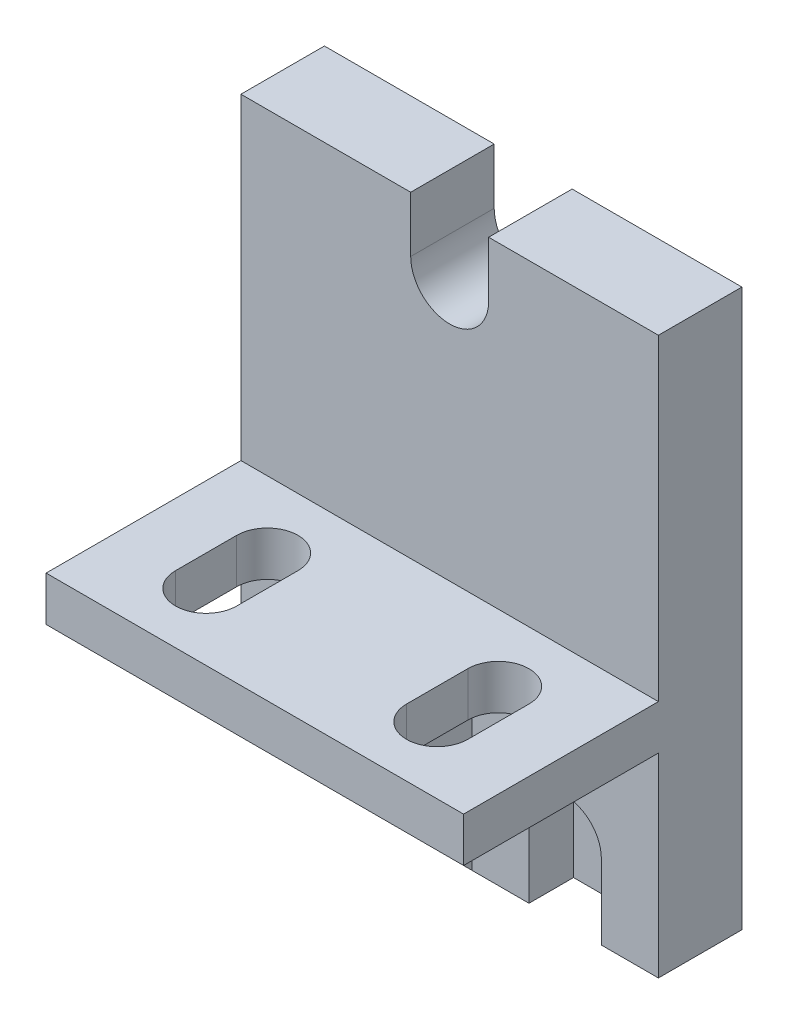
SolidWorks part; units mm, degrees
ref_plane "Спереди" through (0, 0, 0) normal (0, 0, 1) x (1, 0, 0)
ref_plane "Сверху" through (0, 0, 0) normal (0, 1, 0) x (1, 0, 0)
ref_plane "Справа" through (0, 0, 0) normal (1, 0, 0) x (0, 0, -1)
sketch "Эскиз1" plane through (0, 0, 0) normal (0, 0, 1) x (1, 0, 0)
  line L1 (-37.5, -50) -> (37.5, -50)
  line L2 (-37.5, -50) -> (-37.5, 50)
  line L3 (-37.5, 50) -> (37.5, 50)
  line L4 (37.5, -50) -> (37.5, 50)
  line L5 (-37.5, -50) -> (37.5, 50) construction
  line L6 (-37.5, 50) -> (37.5, -50) construction
  point P0 (0, 0)
  dimension "D1" = 75
  dimension "D2" = 100
extrude "Бобышка-Вытянуть1" add sketch "Эскиз1" along normal blind 15
sketch "Эскиз2" plane through (0, 0, 15) normal (0, 0, 1) x (1, 0, 0)
  line L0 (37.5, -50) -> (37.5, 50) construction
  line L1 (-37.5, -15) -> (37.5, -15)
  line L2 (-37.5, -15) -> (-37.5, -7)
  line L3 (-37.5, -7) -> (37.5, -7)
  line L4 (37.5, -15) -> (37.5, -7)
  line L5 (-37.5, -15) -> (37.5, -7) construction
  line L6 (-37.5, -7) -> (37.5, -15) construction
  line L7 (-37.5, -50) -> (37.5, -50) construction
  point P0 (0, -11)
  dimension "D1" = 8
  dimension "D2" = 35
extrude "Бобышка-Вытянуть2" add sketch "Эскиз2" along normal blind 35
sketch "Эскиз3" plane through (0, 0, 0) normal (1, 0, 0) x (0, 0, -1)
  line L0 (-50, -15) -> (-15, -50)
  line L1 (-50, -15) -> (-15, -15)
  line L2 (-15, -15) -> (-15, -50)
extrude "Бобышка-Вытянуть3" add sketch "Эскиз3" along normal mid plane 8
sketch "Эскиз4" plane through (0, -15, 0) normal (0, -1, 0) x (1, 0, 0)
  line L0 (20.75, 50) -> (20.75, 15) construction
  line L1 (4, 50) -> (37.5, 50) construction
  line L2 (4, 15) -> (37.5, 15) construction
  line L3 (20.75, 27) -> (20.75, 38) construction
  line L4 (15.25, 27) -> (15.25, 38)
  line L5 (26.25, 27) -> (26.25, 38)
  arc A0 (15.25, 27) -> (26.25, 27) centre (20.75, 27) ccw
  arc A1 (26.25, 38) -> (15.25, 38) centre (20.75, 38) ccw
  point P8 (20.75, 32.5)
  dimension "D1" = 11
  dimension "D2" = 11
extrude "Вырез-Вытянуть1" cut sketch "Эскиз4" against normal through all
sketch "Эскиз5" plane through (0, 0, 15) normal (0, 0, 1) x (1, 0, 0)
  line L0 (20.75, -63.5) -> (20.75, -36.5) construction
  line L1 (4, -50) -> (37.5, -50) construction
  line L2 (14.25, -63.5) -> (14.25, -36.5)
  line L3 (27.25, -63.5) -> (27.25, -36.5)
  arc A0 (14.25, -63.5) -> (27.25, -63.5) centre (20.75, -63.5) ccw
  arc A1 (27.25, -36.5) -> (14.25, -36.5) centre (20.75, -36.5) ccw
  point P4 (20.75, -50)
  dimension "D1" = 13
  dimension "D2" = 27
extrude "Вырез-Вытянуть2" cut sketch "Эскиз5" against normal blind 8
sketch "Эскиз6" plane through (0, 0, 15) normal (0, 0, 1) x (1, 0, 0)
  line L0 (0, 60) -> (0, 40) construction
  line L1 (37.5, 50) -> (-37.5, 50) construction
  line L2 (7, 60) -> (7, 40)
  line L3 (-7, 60) -> (-7, 40)
  arc A0 (7, 60) -> (-7, 60) centre (0, 60) ccw
  arc A1 (-7, 40) -> (7, 40) centre (0, 40) ccw
  point P5 (0, 50)
  dimension "D1" = 20
  dimension "D2" = 14
extrude "Вырез-Вытянуть3" cut sketch "Эскиз6" against normal through all
mirror "Зеркальное отражение1" about plane through (0, 0, 0) normal (1, 0, 0) of "Вырез-Вытянуть1", "Вырез-Вытянуть2"
